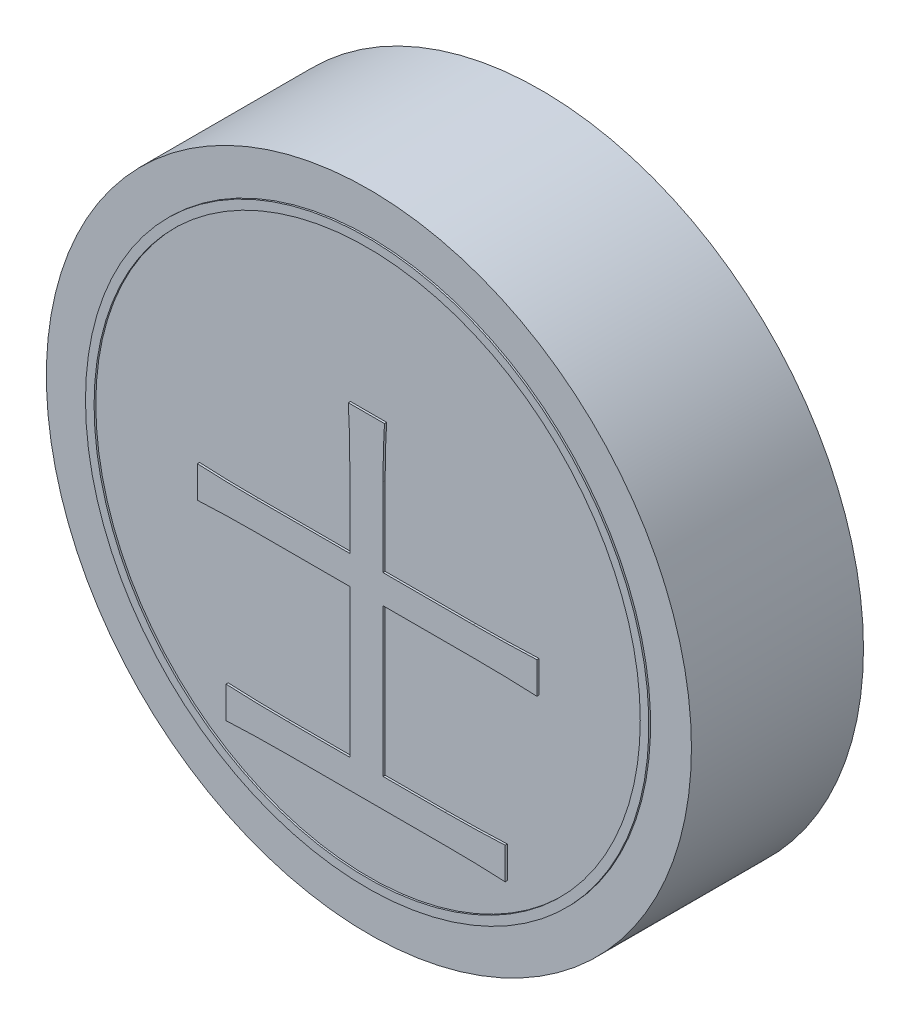
SolidWorks part; units mm, degrees
ref_plane "前视基准面" through (0, 0, 0) normal (0, 0, 1) x (1, 0, 0)
ref_plane "上视基准面" through (0, 0, 0) normal (0, 1, 0) x (1, 0, 0)
ref_plane "右视基准面" through (0, 0, 0) normal (1, 0, 0) x (0, 0, -1)
other "Configuration Table"
sketch "草图1" plane through (0, 0, 0) normal (0, 0, 1) x (1, 0, 0)
  circle A0 centre (0, 0) radius 15
  dimension "D1" = 30
extrude "Diameter30_Height8" add sketch "草图1" against normal blind 8
sketch "草图2" plane through (0, 0, 0) normal (0, 0, 1) x (1, 0, 0)
  text T0 "士" font "SimHei" height 12
extrude "Character_士" add sketch "草图2" along normal blind 0.1
sketch "草图3" plane through (0, 0, 0) normal (0, 0, 1) x (1, 0, 0)
  circle A0 centre (0, 0) radius 13.1
  circle A1 centre (0, 0) radius 12.7
extrude "Ink_ring" add sketch "草图3" along normal blind 0.08
